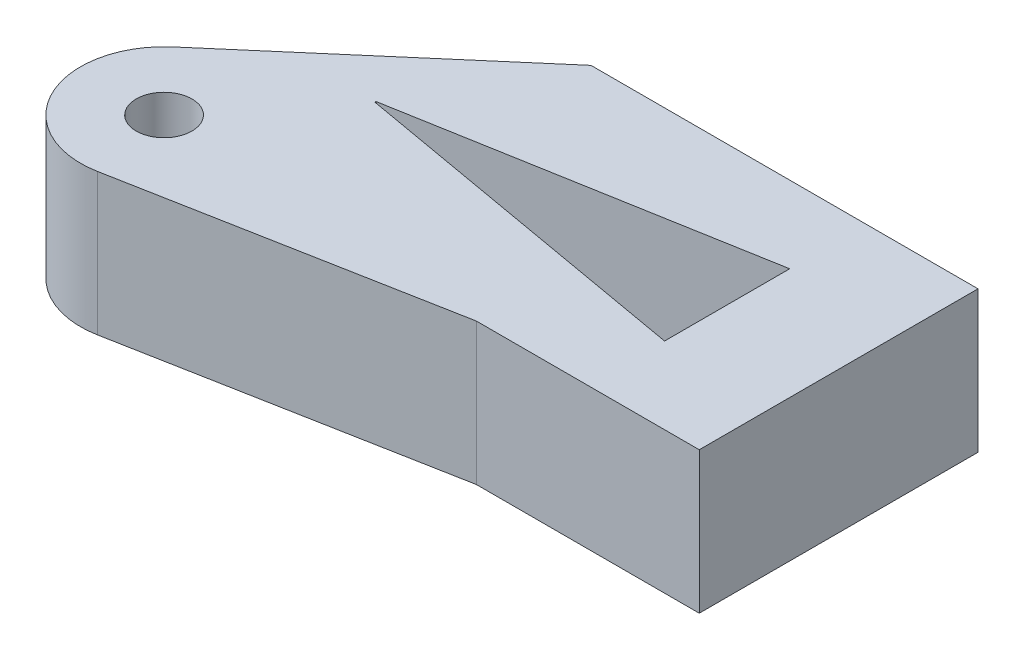
SolidWorks part; units mm, degrees
ref_plane "Front Plane" through (0, 0, 0) normal (0, 0, 1) x (1, 0, 0)
ref_plane "Top Plane" through (0, 0, 0) normal (0, 1, 0) x (1, 0, 0)
ref_plane "Right Plane" through (0, 0, 0) normal (1, 0, 0) x (0, 0, -1)
sketch "Sketch2" plane through (0, 0, 0) normal (0, 1, 0) x (1, 0, 0)
  line L3 (-34.8839, -4.8081) -> (-14.712, 12.5)
  line L4 (-14.712, 12.5) -> (20, 12.5)
  line L5 (20, 12.5) -> (20, -12.5)
  line L15 (-58.3453, 0) -> (-38.0613, 0) construction
  line L16 (-21.542, 0.0513) -> (-21.542, -0.0513)
  line L17 (-21.542, 0.0513) -> (10, 5.6131)
  line L18 (10, 5.6131) -> (10, -5.6131)
  line L19 (10, -5.6131) -> (-21.542, -0.0513)
  line L20 (-21.542, 0.0513) -> (-24.7979, 3.846) construction
  line L21 (-28.6164, -17.8713) -> (0, -12.5)
  line L30 (0, -12.5) -> (20, -12.5)
  circle A0 centre (-30, -10.5) radius 2.5
  arc A1 (-28.6164, -17.8713) -> (-34.8839, -4.8081) centre (-30, -10.5) cw
  circle A2 centre (-30, -10.5) radius 10.5 construction
  point P8 (0, 0)
  point P14 (-21.542, 0)
  point P15 (10, 0)
  point P17 (20, 0)
  dimension "D1" = 5
  dimension "D2" = 10.5
  dimension "D4" = 5
  dimension "D6" = 21
  dimension "D3" = 30
  dimension "D5" = 25
  dimension "D7" = 5
  dimension "D8" = 20
  dimension "D9" = 10
  dimension "D10" = 30
  dimension "D11" = 10
extrude "Boss-Extrude1" add sketch "Sketch2" along normal mid plane 12.7
